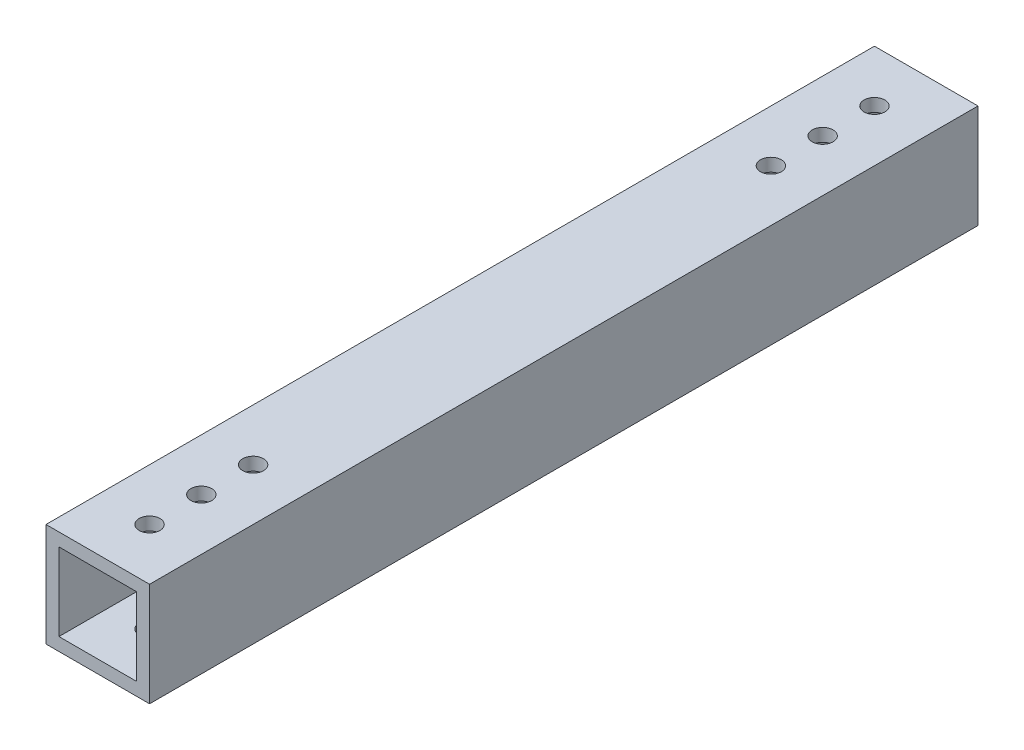
SolidWorks part; units mm, degrees
material "6061 Alloy"
ref_plane "Front" through (0, 0, 0) normal (0, 0, 1) x (1, 0, 0)
ref_plane "Top" through (0, 0, 0) normal (0, 1, 0) x (1, 0, 0)
ref_plane "Right" through (0, 0, 0) normal (1, 0, 0) x (0, 0, -1)
sketch "Sketch1" plane through (0, 0, 0) normal (0, 0, 1) x (1, 0, 0)
  line L1 (0, 0) -> (-25.4, 0)
  line L2 (0, 0) -> (0, 25.4)
  line L3 (0, 25.4) -> (-25.4, 25.4)
  line L4 (-25.4, 0) -> (-25.4, 25.4)
  line L5 (-3.175, 3.175) -> (-22.225, 3.175)
  line L6 (-3.175, 3.175) -> (-3.175, 22.225)
  line L7 (-3.175, 22.225) -> (-22.225, 22.225)
  line L8 (-22.225, 3.175) -> (-22.225, 22.225)
  point P9 (-25.4, 12.7)
  dimension "D1" = 3.175
  dimension "D2" = 3.175
  dimension "D3" = 3.175
  dimension "D4" = 3.175
  dimension "D5" = 25.4
  dimension "D6" = 25.4
extrude "Boss-Extrude1" add sketch "Sketch1" along normal blind 203.2
hole_wizard "#10 Clearance Hole1" positions "Sketch2" profile "Sketch3" hole size "#10" standard "ANSI Inch"
sketch "Sketch2" plane through (0, 25.4, 0) normal (0, 1, 0) x (1, 0, 0)
  line L1 (0, -203.2) -> (-25.4, -203.2) construction
  line L2 (-25.4, -203.2) -> (-25.4, 0) construction
  line L3 (0, 0) -> (-25.4, 0) construction
  point P0 (-12.7, -165.1)
  point P2 (-12.7, -177.8)
  point P4 (-12.7, -190.5)
  point P20 (-12.7, -12.7)
  point P22 (-12.7, -25.4)
  point P24 (-12.7, -38.1)
  dimension "D1" = 12.7
  dimension "D2" = 12.7
  dimension "D3" = 12.7
  dimension "D4" = 12.7
  dimension "D5" = 12.7
  dimension "D6" = 12.7
  dimension "D7" = 12.7
sketch "Sketch3" plane through (-12.7, 25.4, 165.1) normal (1, 0, 0) x (0, 0, 1)
  line L0 (0, 0) -> (0, 26.9328)
  line L1 (0, 26.9328) -> (2.5527, 25.399)
  line L2 (2.5527, 25.399) -> (2.5527, 0)
  line L5 (2.5527, 0) -> (0, 0)
  line L10 (0, 26.9328) -> (-2.5527, 25.399) construction
  line L11 (0, -6.35) -> (0, 107.95) construction
  dimension "Hole Dia." = 5.1054
  dimension "Hole Depth" = 25.399
  dimension "Drill Angle" = 118
